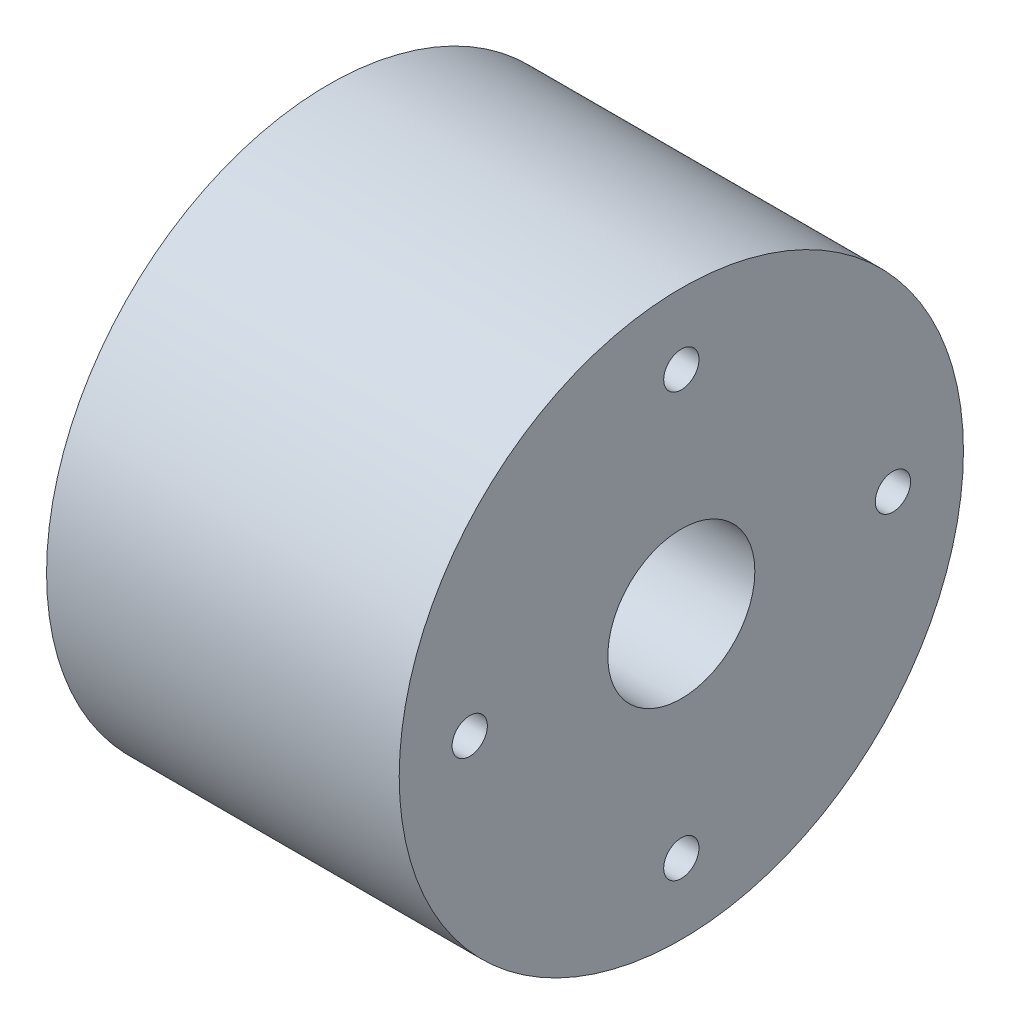
SolidWorks part; units mm, degrees
ref_plane "Front Plane" through (0, 0, 0) normal (0, 0, 1) x (1, 0, 0)
ref_plane "Top Plane" through (0, 0, 0) normal (0, 1, 0) x (1, 0, 0)
ref_plane "Right Plane" through (0, 0, 0) normal (1, 0, 0) x (0, 0, -1)
sketch "Sketch1" plane through (0, 0, 0) normal (1, 0, 0) x (0, 0, -1)
  circle A0 centre (0, 0) radius 40
  dimension "D1" = 80
extrude "Boss-Extrude1" add sketch "Sketch1" along normal blind 50
sketch "Sketch2" plane through (50, 0, 0) normal (1, 0, 0) x (0, 0, -1)
  circle A0 centre (0, 0) radius 10.425
  dimension "D1" = 20.85
extrude "Cut-Extrude1" cut sketch "Sketch2" against normal blind 30
sketch "Sketch3" plane through (0, 0, 0) normal (-1, 0, 0) x (0, 0, 1)
  circle A0 centre (0, 0) radius 20
  circle A1 centre (0, 0) radius 10
  dimension "D1" = 40
  dimension "D2" = 20
extrude "Cut-Extrude2" cut sketch "Sketch3" against normal blind 5
sketch "Sketch4" plane through (0, 0, 0) normal (-1, 0, 0) x (0, 0, 1)
  circle A0 centre (0, 0) radius 0.5
  dimension "D1" = 1
sketch "Sketch5" plane through (0, 0, 0) normal (-1, 0, 0) x (0, 0, 1)
  circle A0 centre (0, 0) radius 30 construction
  circle A1 centre (0, 30) radius 2.5
  circle A2 centre (30, 0) radius 2.5
  circle A3 centre (0, -30) radius 2.5
  circle A4 centre (-30, 0) radius 2.5
  point P14 (0, 0)
  dimension "D1" = 5
  dimension "D2" = 4
extrude "Cut-Extrude4" cut sketch "Sketch5" against normal through all
sketch "Sketch6" plane through (0, 0, 0) normal (0, 0, 1) x (1, 0, 0)
  line L0 (-60.0242, 0) -> (54.9833, 0) construction
  line L1 (0, 13.9892) -> (30, 0) construction
  line L2 (0, 20) -> (0, -20) construction
  line L3 (30, 0) -> (0, -13.9892) construction
  line L4 (20, 0) -> (29.3906, 15.6287) construction
  line L5 (20, -10.425) -> (20, 10.425) construction
  line L6 (20, 0) -> (28.5591, -14.2447) construction
  point P4 (-2.5204, 0)
  dimension "D1" = 25
  dimension "D2" = 25
  dimension "D3" = 30
  dimension "D4" = 33.1013
  dimension "D5" = 59
  dimension "D6" = 59
  dimension "D7" = 118
sketch3d "3DSketch2"
  line L0 (0, 13.9892, 0) -> (30, 0, 0) construction
sketch "Sketch7" plane through (0, 0, 0) normal (-0.9063, 0.4226, 0) x (0, 0, 1)
  line L0 (0, 12.6785) -> (0, -12.6785) construction
  line L1 (0, -25.3673) -> (0, 23.237) construction
  circle A0 centre (0, 12.6785) radius 1.25
  dimension "D1" = 2.5
sketch "Sketch8" plane through (0, 0, 0) normal (0, 0, 1) x (1, 0, 0)
  line L3 (20, 0) -> (29.3906, 15.6287) construction
  line L4 (27.456, 12.4089) -> (20.1841, 0.3064)
  line L5 (19.1513, 0.3064) -> (20.1841, 0.3064)
  line L6 (20, 0) -> (28.5591, -14.2447) construction
  line L7 (27.456, 12.4089) -> (19.1513, 12.4089)
  line L8 (19.1513, 12.4089) -> (19.1513, 0.3064)
  dimension "D1" = 118
revolve "Revolve4" add sketch "Sketch8" angle 360 about L0
extrude "Cut-Extrude6" cut sketch "Sketch4" against normal through all
extrude "Cut-Extrude7" cut sketch "Sketch7" against normal up to next and the other way up to next
mirror "Mirror1" about plane through (0, 0, 0) normal (0, 1, 0) of "Cut-Extrude7"
